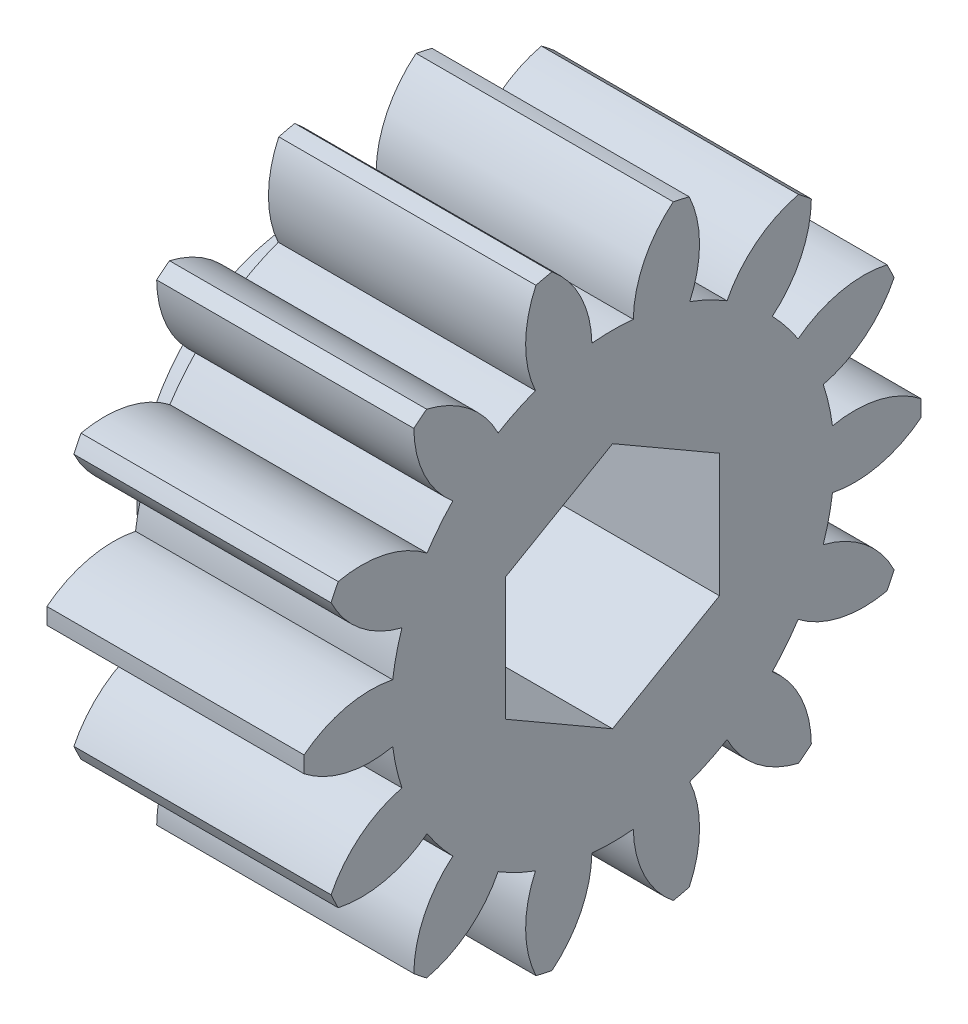
SolidWorks part; units mm, degrees
material "AISI 4340 Aço, normalizado"
ref_plane "Plane1" through (0, 0, 0) normal (0, 0, 1) x (1, 0, 0)
ref_plane "Plane2" through (0, 0, 0) normal (0, 1, 0) x (1, 0, 0)
ref_plane "Plane3" through (0, 0, 0) normal (1, 0, 0) x (0, 0, -1)
sketch "HoldingSke" plane through (0, 0, 0) normal (0, 1, 0) x (1, 0, 0)
  line L0 (0, 0) -> (0.6469, -0.1613)
  line L1 (-15, 0) -> (100, 0) construction
  line L2 (0, 0) -> (-2.1039, 2.3779)
  line L3 (0, 0) -> (-11.863, 4.5341)
  line L4 (0, 0) -> (8.3795, 2.0892)
  line L5 (0, 0) -> (-46.8476, -17.4728)
  line L6 (0, 0) -> (-12.4344, -8.3896)
  line L7 (-2.1039, 2.3779) -> (8.6586, 51.2059)
  line L8 (-76.2, 54.61) -> (-74.8, 54.61)
  line L9 (-71.009, 38.7566) -> (-53.1078, 45.2721)
  line L10 (-76.2, 71.12) -> (104.1128, 71.12)
  line L11 (0, 0) -> (-15, 0)
  line L12 (-76.2, 101.6) -> (-76.147, 101.6)
  line L13 (24.9733, 27.94) -> (52.9518, 28.4284)
  line L14 (24.9733, 27.94) -> (24.9743, 27.94)
  line L15 (24.9733, 27.94) -> (100.4006, 29.5858)
  line L16 (-63.627, -1.5) -> (-12.827, -1.5)
  circle A0 centre (0, 0) radius 4
  circle A1 centre (0, 0) radius 8.624
  circle A2 centre (0, 0) radius 37.5
  circle A3 centre (0, 0) radius 4
  dimension "MHD" = 17.248
  dimension "Hub_dia" = 75
  dimension "Bore" = 8
  dimension "MBD" = 8
  dimension "Num_teeth" = 14
  dimension "Pitch" = 0.6667
  dimension "Overall_len" = 50
  dimension "Show_teeth" = 14
  dimension "Thickness" = 15
  dimension "OAL" = 50.0001
  dimension "T_dim" = 1.4
  dimension "Ap" = 20
  dimension "H" = 19.05
  dimension "Pitch_radius" = 180.3128
  dimension "Width" = 15
  dimension "Backlash" = 0.053
  dimension "Addendum_fac" = 1
  dimension "Dedendum_fac" = 1.25
  dimension "Clearance_fac" = 0.25
  dimension "Dedendum_add" = 0.001
  dimension "Module" = 1.5
sketch "BasProSke" plane through (0, 0, 0) normal (0, 1, 0) x (1, 0, 0)
  line L0 (-10, 0) -> (60, 0) construction
  line L1 (0, 0) -> (0, 12)
  line L2 (0, 0) -> (15, 0)
  line L3 (15, 0) -> (15, 12)
  line L4 (15, 12) -> (0, 12)
  dimension "Thickness" = 15
  dimension "Diameter" = 24
revolve "Base-Revolve" add sketch "BasProSke" angle 360 about L0
sketch "TooCutSke" plane through (0, 0, 0) normal (1, 0, 0) x (0, 0, -1)
  line L1 (0, 0) -> (0, 107) construction
  line L2 (0, 0) -> (-1.2683, 10.4231) construction
  line L3 (0, 0) -> (-4.648, 20.3643) construction
  line L4 (-1.2683, 10.4231) -> (-2.324, 10.1822) construction
  arc A0 (0.8048, 8.5864) -> (-0.8048, 8.5864) centre (0, 0) ccw
  arc A1 (2.3844, 11.7866) -> (-2.3844, 11.7866) centre (0, 0) ccw
  circle A2 centre (0, 0) radius 10.5 construction
  circle A3 centre (0, 0) radius 9.8668 construction
  arc A4 (-0.8048, 8.5864) -> (-2.3844, 11.7866) centre (-5.004, 8.5037) ccw
  arc A5 (2.3844, 11.7866) -> (0.8048, 8.5864) centre (5.004, 8.5037) ccw
  dimension "Root_dia" = 17.248
  dimension "Overcut_dia" = 24.0508
  dimension "Pitch_dia" = 21
  dimension "Base_dia" = 19.7335
  dimension "Flank_rad" = 4.2
  dimension "Half_ang" = 12.857
  dimension "Half_CT" = 1.0829
extrude "ToothCut" cut sketch "TooCutSke" along normal through all
fillet "Breaks" [suppressed] radius 0.03
fillet "RootFillets" [suppressed] radius 0.376
pattern_circular "TeethCuts" count 14 every 25.714 about axis through (-10, 0, 0) along (1, 0, 0) of "ToothCut", "RootFillets", "Breaks"
sketch "HubNeaOneSke" plane through (0, 0, 0) normal (-1, 0, 0) x (0, 0, 1)
  circle A0 centre (0, 0) radius 8.624
  dimension "Diameter" = 17.248
extrude "HubNearOne" [suppressed] add sketch "HubNeaOneSke" along normal blind 35.0001
sketch "HubNeaBotSke" plane through (0, 0, 0) normal (-1, 0, 0) x (0, 0, 1)
  circle A0 centre (0, 0) radius 8.624
  dimension "Diameter" = 17.248
extrude "HubNearBoth" [suppressed] add sketch "HubNeaBotSke" along normal blind 17.5
ref_plane "FarPln" through (15, 0, 0) normal (1, 0, 0) x (0, 0, -1)
sketch "HubFarSke" plane through (15, 0, 0) normal (1, 0, 0) x (0, 0, -1)
  circle A0 centre (0, 0) radius 8.624
  dimension "Diameter" = 17.248
extrude "HubFar" [suppressed] add sketch "HubFarSke" along normal blind 17.5
sketch "BorSke" plane through (0, 0, 0) normal (1, 0, 0) x (0, 0, -1)
  circle A0 centre (0, 0) radius 4
  dimension "Diameter" = 8
extrude "Bore" cut sketch "BorSke" along normal mid plane 100.0001
sketch "KeySke" plane through (0, 0, 0) normal (1, 0, 0) x (0, 0, -1)
  line L0 (-1.5, 0) -> (-1.5, 5.4)
  line L1 (-1.5, 5.4) -> (1.5, 5.4)
  line L2 (1.5, 5.4) -> (1.5, 0)
  line L3 (0, 0) -> (0, 34) construction
  line L4 (-1.5, 0) -> (1.5, 0)
  dimension "Offset" = 5.4
  dimension "Width" = 3
extrude "Keyway" [suppressed] cut sketch "KeySke" along normal mid plane 100.0001
pattern_circular "Keyway2" [suppressed] count 2 every 90 about axis through (-10, 0, 0) along (1, 0, 0)
sketch "Esboço3" plane through (15, 0, 0) normal (1, 0, 0) x (0, 0, -1)
  circle A0 centre (0, 0) radius 4
  circle A1 centre (0, 0) radius 3
  dimension "D1" = 8
  dimension "D2" = 6
extrude "Ressalto-extrusão2" add sketch "Esboço3" against normal up to surface (15 mm away) up to face at (0, 0, -4)
sketch "Esboço4" plane through (15, 0, 0) normal (1, 0, 0) x (0, 0, -1)
  circle A0 centre (0, 0) radius 14.2502
extrude "Corte-extrusão2" cut sketch "Esboço4" against normal blind 5
sketch "Esboço5" plane through (0, 0, 0) normal (-1, 0, 0) x (0, 0, 1)
  line L0 (0, 4.8) -> (0, 0) construction
  line L1 (4.1569, 2.4) -> (0, 4.8)
  line L2 (0, 4.8) -> (-4.1569, 2.4)
  line L3 (-4.1569, 2.4) -> (-4.1569, -2.4)
  line L4 (-4.1569, -2.4) -> (0, -4.8)
  line L5 (0, -4.8) -> (4.1569, -2.4)
  line L6 (4.1569, -2.4) -> (4.1569, 2.4)
  line L7 (0, 0) -> (3, 0) construction
  circle A0 centre (0, 0) radius 3 construction
  circle A1 centre (0, 0) radius 3 construction
  circle A2 centre (0, 0) radius 4 construction
  dimension "D3" = 8
  dimension "D1" = 90
  dimension "D2" = 4.8
extrude "Corte-extrusão3" cut sketch "Esboço5" against normal through all
sketch "Esboço6" plane through (0, 0, 0) normal (-1, 0, 0) x (0, 0, 1)
  circle A0 centre (0, 0) radius 6
  circle A2 centre (0, 0) radius 5
  dimension "D1" = 10
  dimension "D2" = 12
extrude "Ressalto-extrusão3" [suppressed] add sketch "Esboço6" along normal blind 1
sketch "Esboço7" plane through (0, 0, 0) normal (-1, 0, 0) x (0, 0, 1)
  line L0 (0, 0) -> (0, 4.8) construction
  line L1 (0, 4.8) -> (-4.1569, 2.4)
  line L2 (-4.1569, 2.4) -> (-4.1569, -2.4)
  line L3 (-4.1569, -2.4) -> (0, -4.8)
  line L4 (0, -4.8) -> (4.1569, -2.4)
  line L5 (4.1569, -2.4) -> (4.1569, 2.4)
  line L6 (4.1569, 2.4) -> (0, 4.8)
  circle A0 centre (0, 0) radius 6.5
  circle A1 centre (0, 0) radius 4.1569 construction
  dimension "D1" = 13
  dimension "D2" = 4.1569
extrude "Ressalto-extrusão4" add sketch "Esboço7" along normal blind 2
equation "' \"Module@HoldingSke\" = 6.35"
equation "' \"Num_teeth@HoldingSke\" = 12"
equation "' \"Ap@HoldingSke\" =  20"
equation "' \"Ap@HoldingSke\" = 20"
equation "' \"Width@HoldingSke\" = 0.5 * 25.4"
equation "' \"Hub_dia@HoldingSke\"= 1 * 25.4"
equation "' \"Hub_dia@HoldingSke\" = 1 * 25.4"
equation "' \"Overall_len@HoldingSke\" = 1.0 * 25.4"
equation "' \"Bore@HoldingSke\" = 0.75 * 25.4"
equation "' \"T_dim@HoldingSke\" = 0.1 * 25.4"
equation "' \"Width@KeySke\" = 0.25 * 25.4"
equation "' \"Show_teeth@HoldingSke\" = 13"
equation "' \"Backlash@HoldingSke\" = 0.009 * 25.4"
equation "' \"Addendum_fac@HoldingSke\" = 1.0"
equation "' \"Dedendum_fac@HoldingSke\" = 1.25"
equation "' \"Dedendum_add@HoldingSke\" = 0.00005 * 25.4"
equation "' \"Clearance_fac@HoldingSke\" = 0.25"
equation "\"Pitch@HoldingSke\" = 1 / \"Module@HoldingSke\""
equation "\"Overcut_dia@TooCutSke\" = (\"Num_teeth@HoldingSke\" + 2 * \"Addendum_fac@HoldingSke\") / \"Pitch@HoldingSke\" + 0.002 * 25.4"
equation "\"Pitch_dia@TooCutSke\" = \"Num_teeth@HoldingSke\" / \"Pitch@HoldingSke\""
equation "\"Base_dia@TooCutSke\" = \"Num_teeth@HoldingSke\" / \"Pitch@HoldingSke\" * cos((\"Ap@HoldingSke\"  * 3.14159265 / 180))"
equation "\"Root_dia@TooCutSke\" = (\"Num_teeth@HoldingSke\" + 2) / \"Pitch@HoldingSke\" - 2 * (\"Addendum_fac@HoldingSke\" + \"Dedendum_fac@HoldingSke\") / \"Pitch@HoldingSke\" - \"Dedendum_add@HoldingSke\" * 2"
equation "\"Half_ang@TooCutSke\" = 180 / \"Num_teeth@HoldingSke\""
equation "\"Half_CT@TooCutSke\" = \"Num_teeth@HoldingSke\" / \"Pitch@HoldingSke\" * sin((3.14159265 / 2 / \"Num_teeth@HoldingSke\")) / 2 - 7 * \"Backlash@HoldingSke\" / 4"
equation "\"Flank_rad@TooCutSke\" = \"Num_teeth@HoldingSke\" / \"Pitch@HoldingSke\" / 5"
equation "\"Radius@RootFillets\" = \"Clearance_fac@HoldingSke\" / \"Pitch@HoldingSke\" + \"Dedendum_add@HoldingSke\""
equation "\"Break_rad@Breaks\" = 0.02 / \"Pitch@HoldingSke\""
equation "\"Thickness@HoldingSke\" = \"Width@HoldingSke\""
equation "\"OAL@HoldingSke\" = \"Thickness@HoldingSke\""
equation "\"MHD@HoldingSke\" = (\"Num_teeth@HoldingSke\" + 2) / \"Pitch@HoldingSke\" - 2 * (\"Addendum_fac@HoldingSke\" + \"Dedendum_fac@HoldingSke\")  / \"Pitch@HoldingSke\" - \"Dedendum_add@HoldingSke\" * 2"
equation "\"MBD@HoldingSke\" = (\"Num_teeth@HoldingSke\" + 2) / \"Pitch@HoldingSke\" - 2 * (\"Addendum_fac@HoldingSke\" + \"Dedendum_fac@HoldingSke\")  / \"Pitch@HoldingSke\" - \"Dedendum_add@HoldingSke\" * 2 - 0.002 * 25.4"
equation "\"MHD@HoldingSke\" = ((sgn( \"MHD@HoldingSke\" - \"Hub_dia@HoldingSke\" )-1)*( \"MHD@HoldingSke\" - \"Hub_dia@HoldingSke\" ))/-2+ \"Hub_dia@HoldingSke\""
equation "\"MBD@HoldingSke\" = ((sgn( \"MBD@HoldingSke\" - \"Bore@HoldingSke\" )-1)*( \"MBD@HoldingSke\" - \"Bore@HoldingSke\" ))/-2+ \"Bore@HoldingSke\""
equation "\"OAL@HoldingSke\" = ((sgn( \"OAL@HoldingSke\" - \"Overall_len@HoldingSke\" )+1)*( \"OAL@HoldingSke\" - \"Overall_len@HoldingSke\" ))/2 + \"Overall_len@HoldingSke\" + 0.000002 * 25.4"
equation "\"Num_teeth@TeethCuts\" = int( \"Show_teeth@HoldingSke\" ) + 1"
equation "\"Num_teeth@TeethCuts\" = ((sgn( \"Num_teeth@TeethCuts\" - \"Num_teeth@HoldingSke\" )-1)*( \"Num_teeth@TeethCuts\" - \"Num_teeth@HoldingSke\" ))/-2+ \"Num_teeth@HoldingSke\""
equation "\"Num_teeth@TeethCuts\" = ((sgn( \"Num_teeth@TeethCuts\" - 2.0)+1)*( \"Num_teeth@TeethCuts\" - 2.0))/2 +2.0"
equation "\"Angle@TeethCuts\" = 360.0 / \"Num_teeth@HoldingSke\""
equation "\"Diameter@BasProSke\" = (\"Num_teeth@HoldingSke\" + 2 * \"Addendum_fac@HoldingSke\") / \"Pitch@HoldingSke\""
equation "\"Thickness@BasProSke\"  = \"Thickness@HoldingSke\""
equation "' \"Fillet_rad@BasProSke\" =  \"Thickness@HoldingSke\" * 0.05"
equation "' \"Fillet_rad@BasProSke\" = \"Thickness@HoldingSke\" * 0.05"
equation "\"MHD@HoldingSke\" = ((sgn( \"MHD@HoldingSke\" - \"Root_dia@TooCutSke\" )-1)*( \"MHD@HoldingSke\" - \"Root_dia@TooCutSke\" ))/-2+ \"Root_dia@TooCutSke\""
equation "\"Diameter@HubNeaOneSke\" = \"MHD@HoldingSke\""
equation "\"Length@HubNearOne\" = \"OAL@HoldingSke\" - \"Thickness@BasProSke\""
equation "\"Diameter@HubNeaBotSke\" = \"MHD@HoldingSke\""
equation "\"Length@HubNearBoth\" = ( \"OAL@HoldingSke\" - \"Thickness@BasProSke\" ) / 2.0"
equation "\"Thickness@FarPln\" = \"Thickness@BasProSke\""
equation "\"Diameter@HubFarSke\" = \"MHD@HoldingSke\""
equation "\"Length@HubFar\" = ( \"OAL@HoldingSke\" - \"Thickness@BasProSke\" ) / 2.0"
equation "\"Diameter@BorSke\" = \"MBD@HoldingSke\""
equation "\"D1@Bore\" = \"OAL@HoldingSke\" * 2.0"
equation "\"D1@Keyway\" = \"OAL@HoldingSke\" * 2.0"
equation "\"Offset@KeySke\" = \"T_dim@HoldingSke\" + \"MBD@HoldingSke\" / 2.0"
